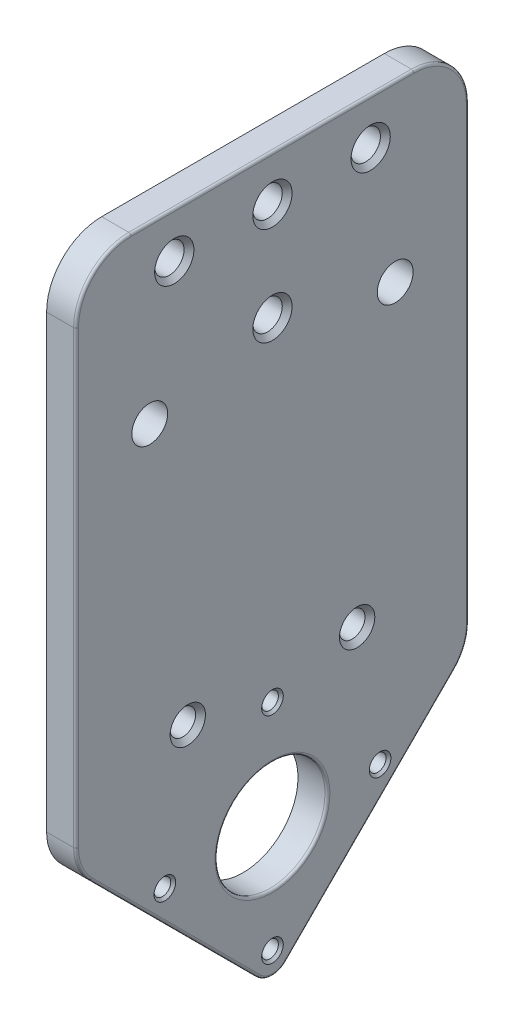
SolidWorks part; units mm, degrees
ref_plane "Спереди (Плоскость XY)" through (0, 0, 0) normal (0, 0, 1) x (1, 0, 0)
ref_plane "Сверху (Плоскость XZ)" through (0, 0, 0) normal (0, 1, 0) x (1, 0, 0)
ref_plane "Справа (Плоскость ZY)" through (0, 0, 0) normal (1, 0, 0) x (0, 0, -1)
sketch "Эскиз2" plane through (0, 0, 0) normal (1, 0, 0) x (0, 0, -1)
  line L0 (-10.5518, -35.8284) -> (10.5656, -56.9458) construction
  line L1 (11.8795, -34.5145) -> (-11.8657, -58.2597) construction
  line L2 (-5.8996, -46.3871) -> (5.818, -46.3871) construction
  line L3 (0, -168.396) -> (0, 124.0583) construction
  line L4 (-28.7833, 72.5422) -> (28.7833, 72.5422)
  line L5 (37.0711, -37.4625) -> (2.8284, -71.7051)
  line L6 (40, 61.3255) -> (40, -30.3914)
  line L141 (-40, 61.3255) -> (-40, -30.3914)
  line L142 (-37.0711, -37.4625) -> (-2.8284, -71.7051)
  circle A1 centre (-21.9134, -46.3871) radius 1.7
  circle A4 centre (17.25, -19.8871) radius 2.6
  circle A5 centre (-17.25, -19.8871) radius 2.6
  circle A6 centre (0.0069, -46.3871) radius 11.2
  circle A7 centre (-25, 37.1129) radius 3.655
  circle A8 centre (-20, 63.3206) radius 3
  circle A9 centre (0, 63.3206) radius 3
  circle A10 centre (0, 43.3206) radius 3
  circle A11 centre (20, 63.3206) radius 3
  circle A12 centre (25, 37.1129) radius 3.655
  circle A13 centre (0.0069, -24.4668) radius 1.7
  circle A14 centre (21.9272, -46.3871) radius 1.7
  circle A15 centre (0.0069, -68.3074) radius 1.7
  arc A18 (-40, 61.3255) -> (-28.7833, 72.5422) centre (-28.7833, 61.3255) cw
  arc A19 (40, 61.3255) -> (28.7833, 72.5422) centre (28.7833, 61.3255) ccw
  arc A20 (37.0711, -37.4625) -> (40, -30.3914) centre (30, -30.3914) ccw
  arc A21 (-40, -30.3914) -> (-37.0711, -37.4625) centre (-30, -30.3914) ccw
  arc A22 (-2.8284, -71.7051) -> (2.8284, -71.7051) centre (0, -68.8767) ccw
  point P0 (-20, 63.3206)
  point P1 (0, 63.3206)
  point P2 (20, 63.3206)
  point P3 (0, 43.3206)
  point P4 (-25, 37.1129)
  point P5 (-17.25, -19.8871)
  point P7 (17.25, -19.8871)
  point P9 (-21.9134, -46.3871)
  point P11 (0.0069, -46.3871)
  point P12 (25, 37.1129)
  point P43 (0.0069, -46.3871)
  point P55 (0, 72.5422)
  point P63 (40, -34.5335)
  point P66 (-40, -34.5335)
  dimension "D1" = 22.4
  dimension "D2" = 3.4
  dimension "D3" = 5.2
  dimension "D4" = 6
  dimension "D10" = 57
  dimension "D18" = 7.31
  dimension "D19" = 90
  dimension "D20" = 10
  dimension "D15" = 4
  dimension "D5" = 31
  dimension "D6" = 90
  dimension "D7" = 45
  dimension "D8" = 31
  dimension "D11" = 26.5
  dimension "D12" = 20
  dimension "D13" = 34.5
  dimension "D14" = 50
  dimension "D16" = 40
  dimension "D17" = 80
  dimension "D9" = 4
extrude "Бобышка-Вытянуть1" add sketch "Эскиз2" along normal blind 6
chamfer "Фаска1" distance 1 angle 45 6 edges at (6, 63.3206, -23) (6, 63.3206, 17) (6, 63.3206, -3) (6, 43.3206, -3) (6, -19.8871, 14.65) (6, -19.8871, -19.85)
chamfer "Фаска2" distance 0.5 angle 45 4 edges at (6, -68.3074, -1.7069) (6, -46.3871, -23.6272) (6, -46.3871, 20.2134) (6, -24.4668, -1.7069)
fillet "Скругление1" radius 0.5 11 edges at (6, 69.2569, -36.7147) (6, 15.4671, -40) (6, -34.2182, -39.2388) (6, -54.5838, -19.9497) (6, -72.8767, 0) (6, -54.5838, 19.9497) (6, -34.2182, 39.2388) (6, 15.4671, 40) (6, 69.2569, 36.7147) (6, 72.5422, 0) (6, -46.3871, -11.2069)
equation "\"deltahole\"= 0.4"
